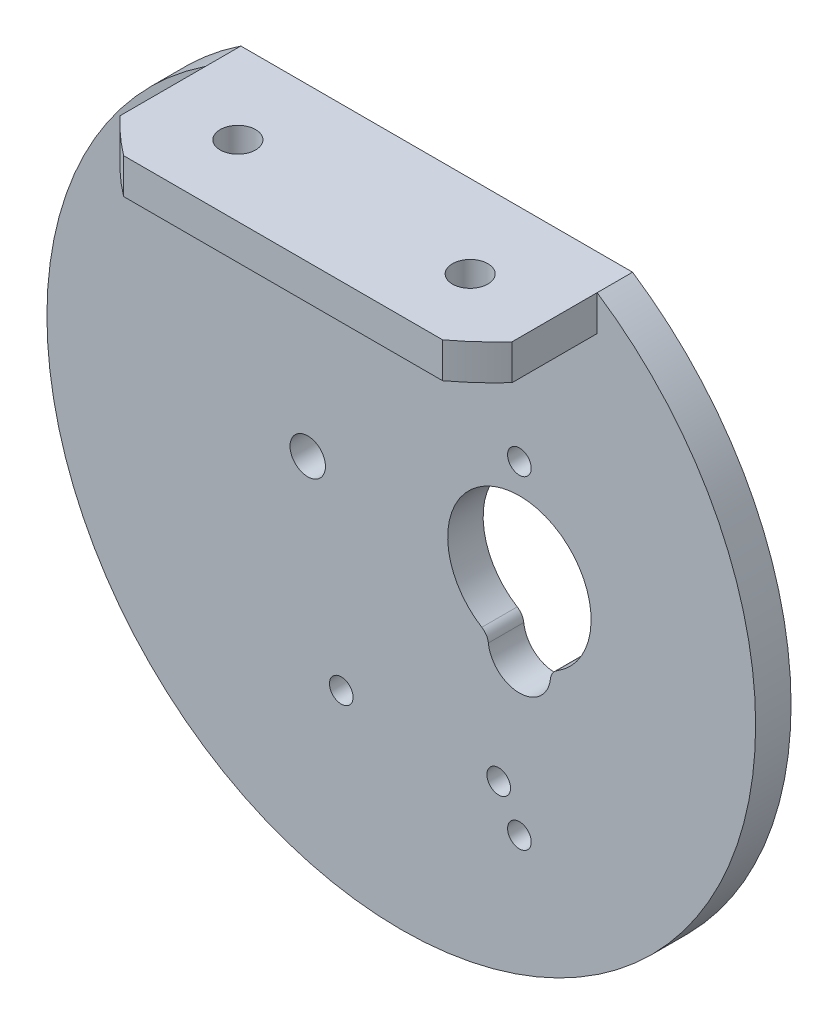
SolidWorks part; units mm, degrees
ref_plane "Plan de face" through (0, 0, 0) normal (0, 0, 1) x (1, 0, 0)
ref_plane "Plan de dessus" through (0, 0, 0) normal (0, 1, 0) x (1, 0, 0)
ref_plane "Plan de droite" through (0, 0, 0) normal (1, 0, 0) x (0, 0, -1)
sketch "Esquisse1" plane through (0, 0, 0) normal (0, 0, 1) x (1, 0, 0)
  line L0 (-16.5831, 25) -> (16.5831, 25)
  circle A0 centre (0, 0) radius 30
  dimension "D1" = 60
  dimension "D2" = 25
extrude "Boss.-Extru.1" add sketch "Esquisse1" along normal blind 3 contours L0 A0
sketch "Esquisse2" plane through (0, 0, 0) normal (0, 0, -1) x (-1, 0, 0)
  line L0 (-16.5831, 22) -> (16.5831, 22)
  line L1 (16.5831, 25) -> (-16.5831, 25)
  line L2 (16.5831, 25) -> (-16.5831, 25)
  line L3 (-16.5831, 25) -> (-16.5831, 22)
  line L4 (16.5831, 25) -> (16.5831, 22)
  arc A1 (-16.5831, 25) -> (16.5831, 25) centre (0, 0) ccw
  arc A2 (-16.5831, 25) -> (16.5831, 25) centre (0, 0) ccw
  line M3 (16.5831, 25) -> (-16.5831, 25)
  arc M4 (-16.5831, 25) -> (16.5831, 25) centre (0, 0) ccw
  dimension "D2" = 3
  dimension "D1" = 0
extrude "Boss.-Extru.2" add sketch "Esquisse2" against normal blind 10 from offset 3 contours L0 M4 M3 offset against normal yes
sketch "Esquisse3" plane through (0, 25, 0) normal (0, 1, 0) x (1, 0, 0)
  line L0 (13.4981, -13) -> (16.5831, -13)
  line L6 (16.5831, 0) -> (-16.5831, 0)
  line L7 (-16.5831, 0) -> (-16.5831, -3)
  line L8 (-16.5831, -3) -> (-16.5831, -13)
  line L9 (-16.5831, -13) -> (16.5831, -13)
  line L10 (16.5831, -13) -> (16.5831, -3)
  line L11 (16.5831, -3) -> (16.5831, 0)
  line L14 (-16.5831, -10.209) -> (-16.5831, -13)
  line L15 (-16.5831, -13) -> (-13.5019, -13)
  line L16 (16.5831, -13) -> (16.5831, -10.2049)
  arc A0 (-16.5831, -10.209) -> (-13.5019, -13) centre (-0.0019, 5) ccw
  arc A1 (13.4981, -13) -> (16.5831, -10.2049) centre (-0.0019, 5) ccw
  dimension "D1" = 0
extrude "Enlèv. mat.-Extru.1" cut sketch "Esquisse3" against normal blind 10
sketch "Esquisse4" plane through (0, 22, 0) normal (0, -1, 0) x (1, 0, 0)
  line L0 (13.4981, 13) -> (-13.5019, 13) construction
  line L1 (-16.5831, 10.209) -> (-16.5831, 3) construction
  line L2 (0, 18.3474) -> (0, -4.7775) construction
  circle A0 centre (-9.8331, 7) radius 1.5
  circle A1 centre (9.8331, 7) radius 1.5
  dimension "D1" = 3
  dimension "D2" = 6
  dimension "D3" = 6.75
extrude "Enlèv. mat.-Extru.2" cut sketch "Esquisse4" against normal blind 10
sketch "Esquisse5" plane through (0, 0, 3) normal (0, 0, 1) x (1, 0, 0)
  circle A0 centre (10, -18.075) radius 1
  circle A1 centre (10, 9.325) radius 1
extrude "Enlèv. mat.-Extru.3" cut sketch "Esquisse5" against normal through all
sketch "Esquisse6" plane through (0, 0, 0) normal (0, 0, -1) x (-1, 0, 0)
  line L0 (16.5831, 25) -> (-16.5831, 25) construction
  arc A4 (-12.6287, -5.2928) -> (-13.1828, -4.4186) centre (-13.8015, -5.4234) ccw
  arc A5 (-6.8172, -4.4186) -> (-13.1828, -4.4186) centre (-10, 0.75) ccw
  arc A6 (-6.8172, -4.4186) -> (-7.3713, -5.2928) centre (-6.1985, -5.4234) ccw
  arc A7 (-12.6287, -5.2928) -> (-7.3713, -5.2928) centre (-10, -5) ccw
  point P0 (0, 0)
  dimension "D2" = 24.25
  dimension "D3" = 10
extrude "Enlèv. mat.-Extru.4" cut sketch "Esquisse6" against normal through all
sketch "Esquisse7" plane through (0, 0, 0) normal (0, 0, -1) x (-1, 0, 0)
  circle A0 centre (7.92, 0.75) radius 1.5
  dimension "D2" = 3
  dimension "D1" = 7.92
extrude "Enlèv. mat.-Extru.5" cut sketch "Esquisse7" against normal through all
sketch "Esquisse8" plane through (0, 0, 0) normal (0, 0, -1) x (-1, 0, 0)
  line L0 (0, 25) -> (0, -30) construction
  line L1 (16.5831, 25) -> (-16.5831, 25) construction
  line L2 (-8.25, -15) -> (5.08, -15) construction
  arc A0 (-16.5831, 25) -> (16.5831, 25) centre (0, 0) ccw construction
  circle A1 centre (-8.25, -15) radius 1
  circle A3 centre (5.08, -15) radius 1
  dimension "D3" = 2
  dimension "D1" = 8.25
  dimension "D2" = 15
  dimension "D4" = 13.33
extrude "Enlèv. mat.-Extru.6" cut sketch "Esquisse8" against normal blind 3
